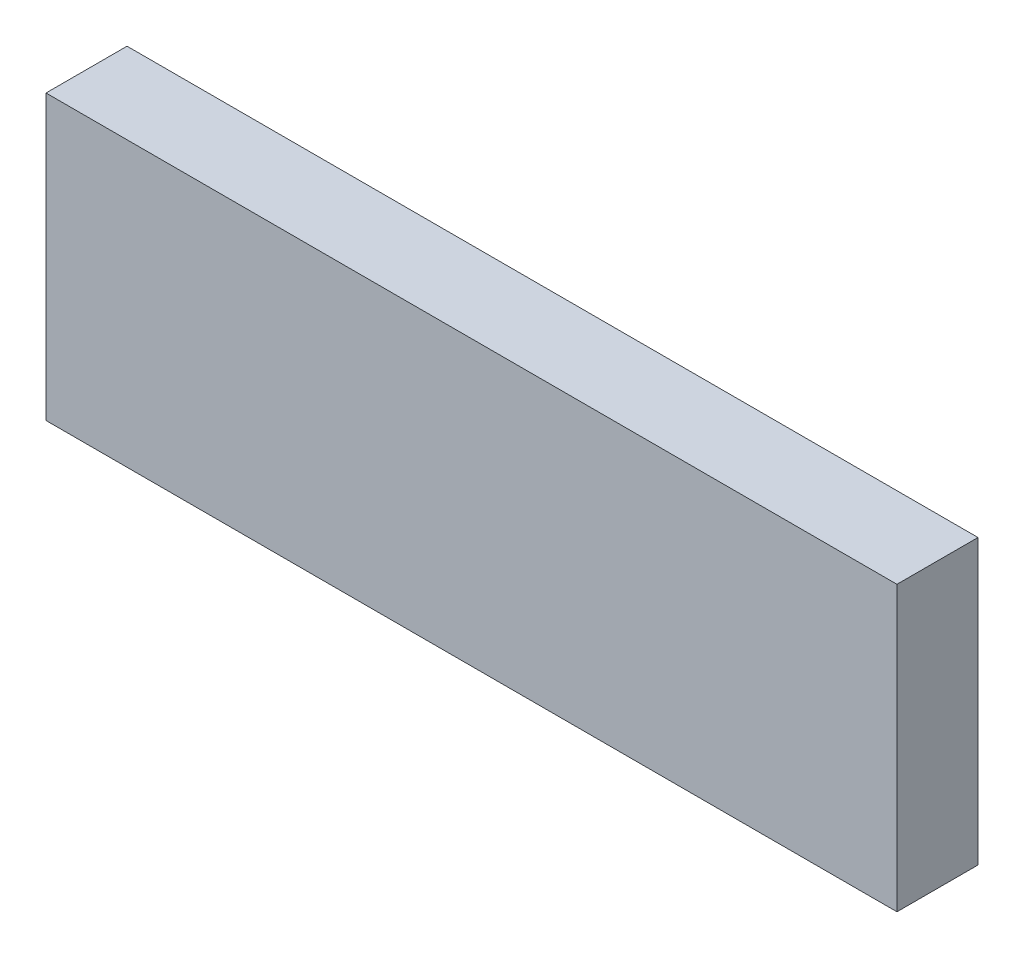
SolidWorks part; units mm, degrees
ref_plane "前视基准面" through (0, 0, 0) normal (0, 0, 1) x (1, 0, 0)
ref_plane "上视基准面" through (0, 0, 0) normal (0, 1, 0) x (1, 0, 0)
ref_plane "右视基准面" through (0, 0, 0) normal (1, 0, 0) x (0, 0, -1)
other "Configuration Table"
sketch "草图1" plane through (0, 0, 0) normal (0, 0, 1) x (1, 0, 0)
  line L1 (-105, -35) -> (105, -35)
  line L2 (-105, -35) -> (-105, 35)
  line L3 (-105, 35) -> (105, 35)
  line L4 (105, -35) -> (105, 35)
  line L5 (-105, -35) -> (105, 35) construction
  line L6 (-105, 35) -> (105, -35) construction
  point P0 (0, 0)
extrude "凸台-拉伸1" add sketch "草图1" along normal blind 20
